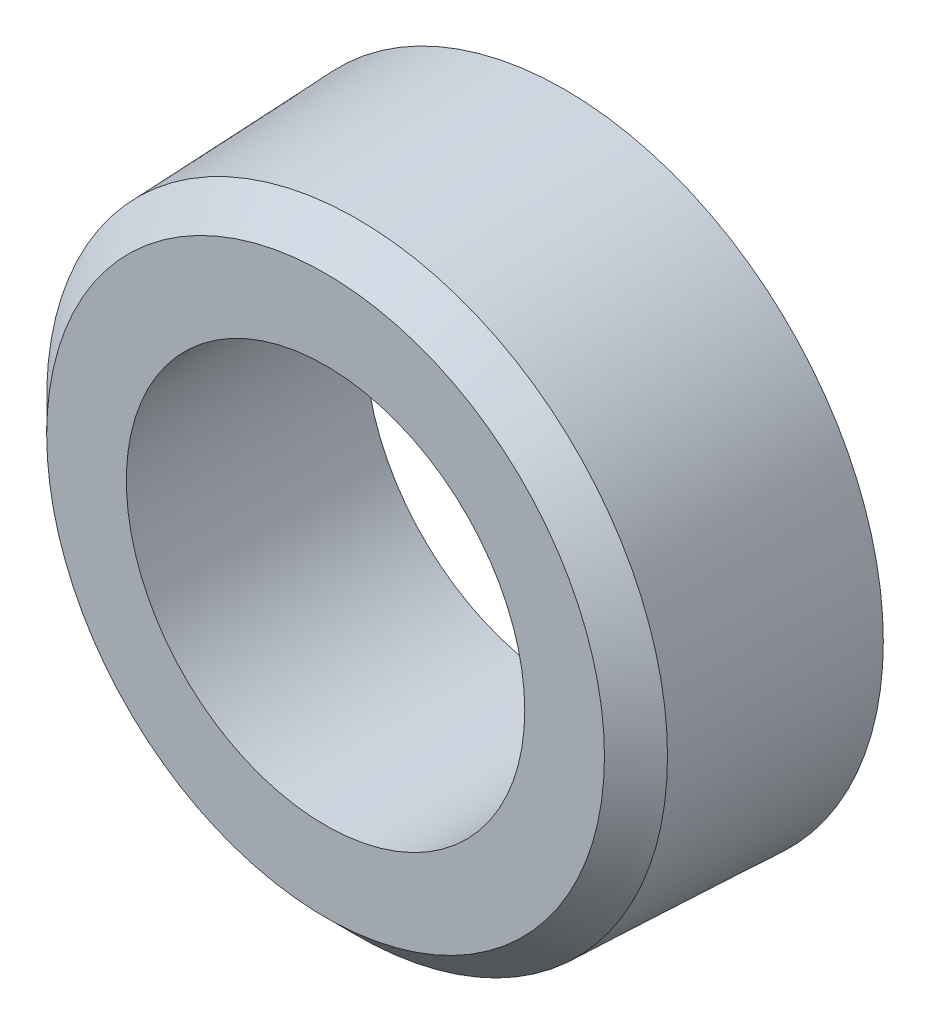
SolidWorks part; units mm, degrees
ref_plane "Спереди" through (0, 0, 0) normal (0, 0, 1) x (1, 0, 0)
ref_plane "Сверху" through (0, 0, 0) normal (0, 1, 0) x (1, 0, 0)
ref_plane "Справа" through (0, 0, 0) normal (1, 0, 0) x (0, 0, -1)
sketch "Эскиз1" plane through (0, 0, 0) normal (0, 0, 1) x (1, 0, 0)
  circle A0 centre (0, 0) radius 8
  circle A1 centre (0, 0) radius 5
  dimension "D1" = 3
  dimension "D2" = 16
extrude "Вытянуть1" add sketch "Эскиз1" along normal blind 6
ref_axis "Ось1" through (0, 0, 6) along (0, 0, -1)
chamfer "Фаска1" distance 1 angle 45 1 edges at (8, 0, 6)
sketch "Эскиз4" plane through (0, 0, 0) normal (1, 0, 0) x (0, 0, -1)
  line L0 (0, 8) -> (-6, 7.76)
  line L2 (-6, 7.76) -> (-6, 8)
  line L3 (-6, 8) -> (0, 8)
  line L5 (-6, 7) -> (-6, -7) construction
  line L6 (-5, 8) -> (-5, 7.8) construction
  line L7 (-5, -8) -> (-5, 8) construction
  line L8 (-6, 0) -> (0, 0) construction
  dimension "D1" = 7.8
revolve "Вырез-Повернуть1" cut sketch "Эскиз4" angle 360 about axis through (0, 0, 6) along (0, 0, -1)
